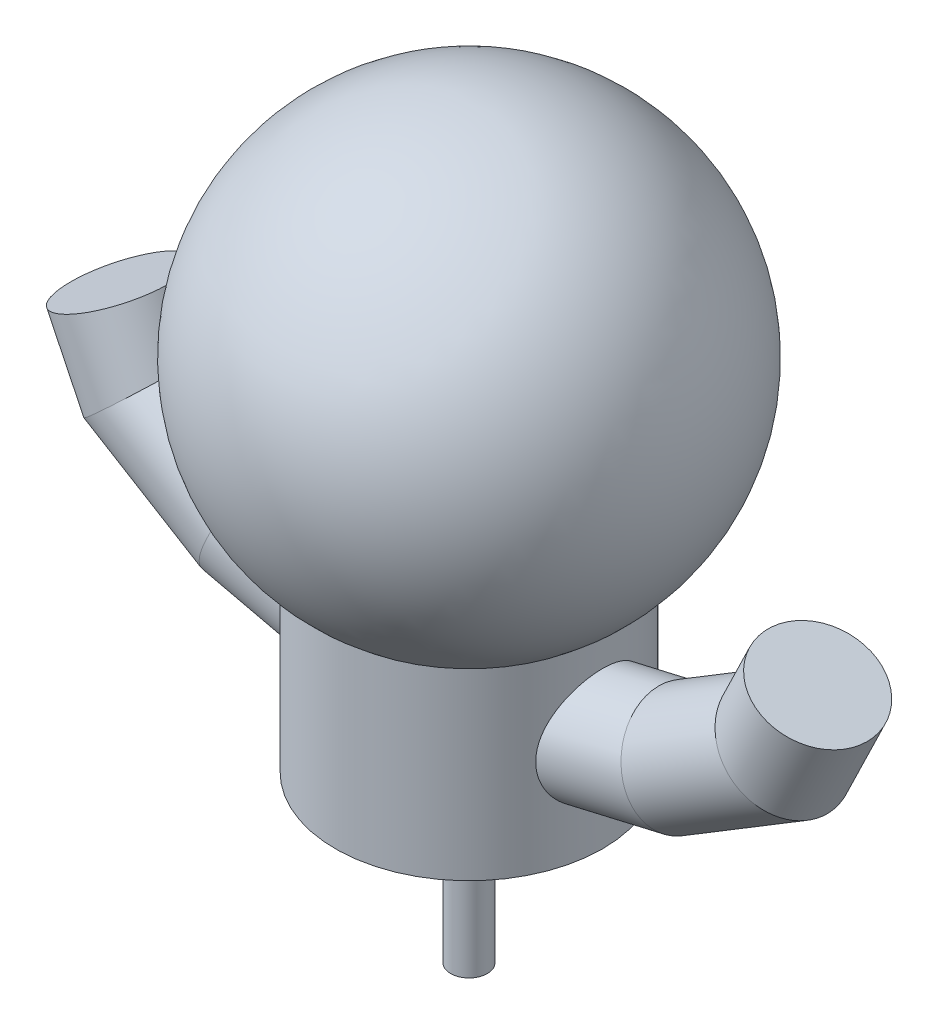
SolidWorks part; units mm, degrees
ref_plane "Plan de face" through (0, 0, 0) normal (0, 0, 1) x (1, 0, 0)
ref_plane "Plan de dessus" through (0, 0, 0) normal (0, 1, 0) x (1, 0, 0)
ref_plane "Plan de droite" through (0, 0, 0) normal (1, 0, 0) x (0, 0, -1)
sketch "Esquisse1" plane through (0, 0, 0) normal (0, 0, 1) x (1, 0, 0)
  line L0 (0, 0) -> (0, 5) construction
  line L1 (0, 5) -> (0, 6)
  line L3 (6.8102, -4.7697) -> (-8.1712, -4.7697) construction
  line L4 (6.8102, -9.7697) -> (-8.1712, -9.7697) construction
  line L5 (3.6401, -4.7697) -> (3.6401, -9.7697)
  line L7 (1.5, -4.7697) -> (0, -4.7697)
  line L9 (0, -4.7697) -> (0, -14.2831)
  line L10 (0, -14.2831) -> (0.5, -14.2831)
  line L11 (0.5, -14.2831) -> (0.5, -9.7697)
  line L12 (0.5, -9.7697) -> (3.6401, -9.7697)
  arc A2 (0, 5) -> (1.5, -4.7697) centre (0, 0) cw
  arc A3 (0, 6) -> (3.6401, -4.7697) centre (0, 0) cw
  dimension "D1" = 5
  dimension "D3" = 1
  dimension "D2" = 4.7697
  dimension "D4" = 5
  dimension "D5" = 0.5
revolve "Révolution4" add sketch "Esquisse1" angle 360 about L0
sketch "Sketch1" plane through (0, 0, 0) normal (0, 0, 1) x (1, 0, 0)
  line L0 (-3.1182, -7.1774) -> (-5.7449, -6.5665)
  line L1 (-5.7449, -6.5665) -> (-8.5956, -4.8358)
  line L2 (0, 0) -> (0, -17.8366) construction
  line L3 (3.1182, -7.1774) -> (5.7449, -6.5665)
  line L4 (5.7449, -6.5665) -> (8.5956, -4.8358)
  line L5 (-3.1182, -7.1774) -> (3.1182, -7.1774)
  line L6 (8.5956, -4.8358) -> (9.4964, -2.9809)
  line L7 (10.0425, -14.2924) -> (-9.9575, -14.2924) construction
  line L8 (10.0425, -14.2924) -> (10.0425, 7.7076) construction
  line L9 (10.0425, 7.7076) -> (-9.9575, 7.7076) construction
  line L10 (-9.9575, -14.2924) -> (-9.9575, 7.7076) construction
  line L11 (-8.5956, -4.8358) -> (-9.4964, -2.9809)
  dimension "D1" = 22
  dimension "D2" = 20
sweep "Sweep1" add path "Sketch1" circular profile diameter 3 parameters "D3"=3
